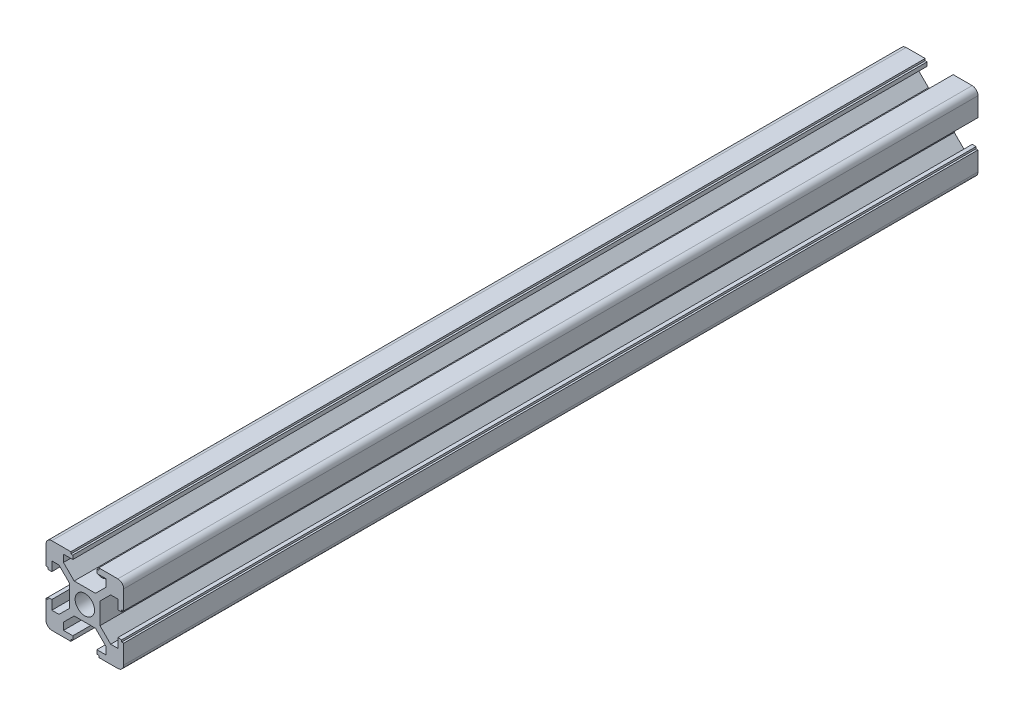
SolidWorks part; units mm, degrees
ref_plane "Plane1" through (0, 0, 0) normal (0, 0, 1) x (1, 0, 0)
ref_plane "Plane2" through (0, 0, 0) normal (0, 1, 0) x (1, 0, 0)
ref_plane "Plane3" through (0, 0, 0) normal (1, 0, 0) x (0, 0, -1)
sketch "Sketch1" plane through (0, 0, 0) normal (0, 0, 1) x (1, 0, 0)
  line L0 (-3.6, 10) -> (-3.6, 9.5)
  line L1 (-3.6, 9.5) -> (-3.1, 9.5)
  line L2 (-3.1, 9.5) -> (-3.1, 8.5)
  line L3 (-3.1, 8.5) -> (-5.5, 8.5)
  line L4 (-8.5, -10) -> (-3.6, -10)
  line L5 (-10, -8.5) -> (-10, -3.6)
  line L6 (8.5, 10) -> (3.6, 10)
  line L7 (10, 8.5) -> (10, 3.6)
  line L8 (0, 14.8756) -> (0, 0) construction
  line L9 (0, 0) -> (14.1675, 0) construction
  line L10 (-5.5, 8.5) -> (-5.5, 6.65)
  line L11 (-5.5, 6.65) -> (-2.75, 3.9)
  line L12 (-2.75, 3.9) -> (2.75, 3.9)
  line L13 (5.5, 6.65) -> (2.75, 3.9)
  line L14 (5.5, 8.5) -> (5.5, 6.65)
  line L15 (3.1, 8.5) -> (5.5, 8.5)
  line L16 (3.1, 9.5) -> (3.1, 8.5)
  line L17 (3.6, 9.5) -> (3.1, 9.5)
  line L18 (3.6, 10) -> (3.6, 9.5)
  line L19 (-3.6, 10) -> (-8.5, 10)
  line L20 (10, 3.6) -> (9.5, 3.6)
  line L21 (9.5, 3.6) -> (9.5, 3.1)
  line L22 (9.5, 3.1) -> (8.5, 3.1)
  line L23 (8.5, 3.1) -> (8.5, 5.5)
  line L24 (8.5, 5.5) -> (6.65, 5.5)
  line L25 (6.65, 5.5) -> (3.9, 2.75)
  line L26 (3.9, 2.75) -> (3.9, -2.75)
  line L27 (6.65, -5.5) -> (3.9, -2.75)
  line L28 (8.5, -5.5) -> (6.65, -5.5)
  line L29 (8.5, -3.1) -> (8.5, -5.5)
  line L30 (9.5, -3.1) -> (8.5, -3.1)
  line L31 (9.5, -3.6) -> (9.5, -3.1)
  line L32 (10, -3.6) -> (9.5, -3.6)
  line L33 (3.6, -10) -> (3.6, -9.5)
  line L34 (3.6, -9.5) -> (3.1, -9.5)
  line L35 (3.1, -9.5) -> (3.1, -8.5)
  line L36 (3.1, -8.5) -> (5.5, -8.5)
  line L37 (5.5, -8.5) -> (5.5, -6.65)
  line L38 (5.5, -6.65) -> (2.75, -3.9)
  line L39 (2.75, -3.9) -> (-2.75, -3.9)
  line L40 (-5.5, -6.65) -> (-2.75, -3.9)
  line L41 (-5.5, -8.5) -> (-5.5, -6.65)
  line L42 (-3.1, -8.5) -> (-5.5, -8.5)
  line L43 (-3.1, -9.5) -> (-3.1, -8.5)
  line L44 (-3.6, -9.5) -> (-3.1, -9.5)
  line L45 (-3.6, -10) -> (-3.6, -9.5)
  line L46 (-10, -3.6) -> (-9.5, -3.6)
  line L47 (-9.5, -3.6) -> (-9.5, -3.1)
  line L48 (-9.5, -3.1) -> (-8.5, -3.1)
  line L49 (-8.5, -3.1) -> (-8.5, -5.5)
  line L50 (-8.5, -5.5) -> (-6.65, -5.5)
  line L51 (-6.65, -5.5) -> (-3.9, -2.75)
  line L52 (-3.9, -2.75) -> (-3.9, 2.75)
  line L53 (-6.65, 5.5) -> (-3.9, 2.75)
  line L54 (-8.5, 5.5) -> (-6.65, 5.5)
  line L55 (-8.5, 3.1) -> (-8.5, 5.5)
  line L56 (-9.5, 3.1) -> (-8.5, 3.1)
  line L57 (-9.5, 3.6) -> (-9.5, 3.1)
  line L58 (-10, 3.6) -> (-9.5, 3.6)
  line L59 (3.6, -10) -> (8.5, -10)
  line L60 (-10, 3.6) -> (-10, 8.5)
  line L61 (10, -3.6) -> (10, -8.5)
  circle A0 centre (0, 0) radius 2.5
  arc A1 (-10, 8.5) -> (-8.5, 10) centre (-8.5, 8.5) cw
  arc A2 (10, 8.5) -> (8.5, 10) centre (8.5, 8.5) ccw
  arc A3 (-8.5, -10) -> (-10, -8.5) centre (-8.5, -8.5) cw
  arc A4 (8.5, -10) -> (10, -8.5) centre (8.5, -8.5) ccw
  point P0 (-10, 0)
  point P1 (10, 0)
  point P2 (0, 10)
  point P3 (0, -10)
  point P4 (0, 0)
  point P5 (-10, -10)
  point P6 (10, -10)
  point P7 (10, 10)
  point P8 (-10, 10)
  point P36 (-10, 10)
  point P39 (10, 10)
extrude "凸台-拉伸1" add sketch "Sketch1" along normal blind 220
sketch "草图1" plane through (0, 3.9, 0) normal (0, 1, 0) x (1, 0, 0)
  line L0 (2.75, -220) -> (-2.75, -220) construction
  circle A0 centre (0, -214) radius 1.7
  circle A1 centre (0, -6) radius 1.7
  point P0 (0, -214)
  dimension "D2" = 2
  dimension "D1" = 6
extrude "切除-拉伸1" cut sketch "草图1" against normal through all
